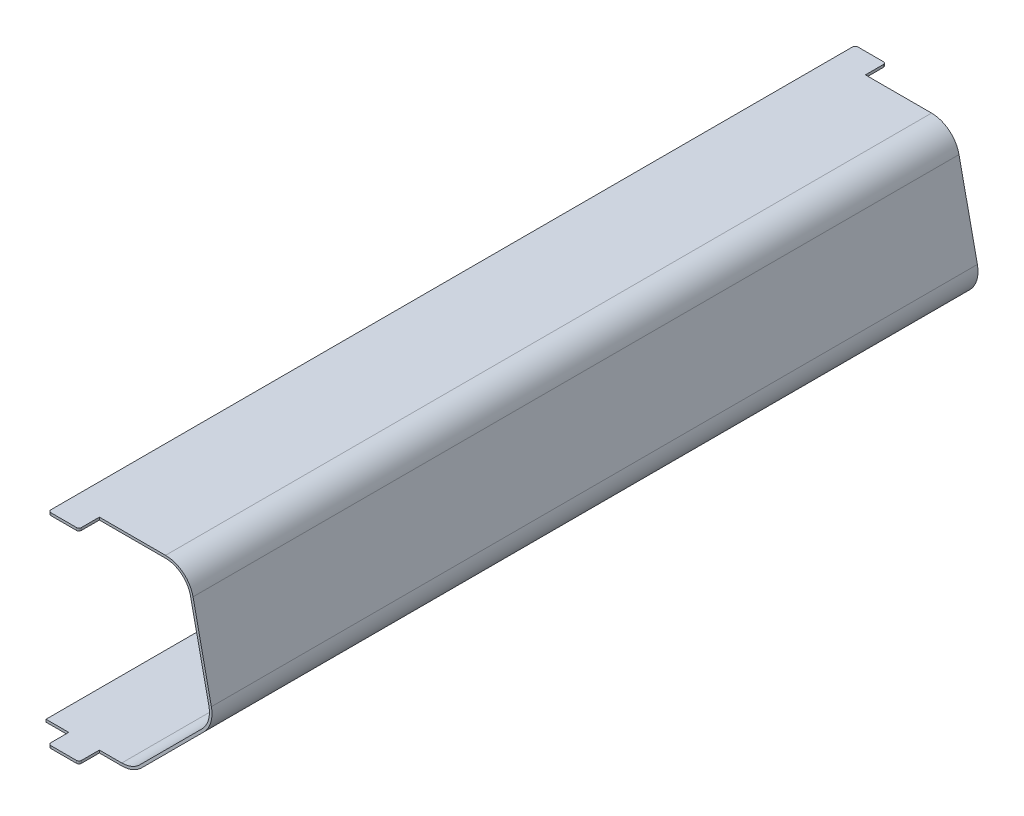
SolidWorks part; units mm, degrees
ref_plane "Front Plane" through (0, 0, 0) normal (0, 0, 1) x (1, 0, 0)
ref_plane "Top Plane" through (0, 0, 0) normal (0, 1, 0) x (1, 0, 0)
ref_plane "Right Plane" through (0, 0, 0) normal (1, 0, 0) x (0, 0, -1)
sketch "Sketch1" plane through (0, 0, 0) normal (0, 0, 1) x (1, 0, 0)
  line L0 (0, 0) -> (14.8381, 0)
  line L1 (18.3737, 1.4645) -> (30.5433, 13.6341)
  line L2 (31.8973, 18.2147) -> (28.3001, 35.0451)
  line L3 (23.4105, 39) -> (4.4547, 39)
  line L4 (0, -0.5) -> (14.8381, -0.5)
  line L5 (18.7272, 1.1109) -> (30.8969, 13.2806)
  line L6 (32.3863, 18.3193) -> (28.789, 35.1496)
  line L7 (23.4105, 39.5) -> (4.4547, 39.5)
  line L8 (4.4547, 39.5) -> (4.4547, 39)
  line L9 (0, 0) -> (0, -0.5)
  arc A0 (28.3001, 35.0451) -> (23.4105, 39) centre (23.4105, 34) ccw
  arc A1 (30.5433, 13.6341) -> (31.8973, 18.2147) centre (27.0078, 17.1697) ccw
  arc A2 (14.8381, 0) -> (18.3737, 1.4645) centre (14.8381, 5) ccw
  arc A3 (14.8381, -0.5) -> (18.7272, 1.1109) centre (14.8381, 5) ccw
  arc A4 (30.8969, 13.2806) -> (32.3863, 18.3193) centre (27.0078, 17.1697) ccw
  arc A5 (28.789, 35.1496) -> (23.4105, 39.5) centre (23.4105, 34) ccw
  point P8 (27.4547, 39)
  point P11 (32.4656, 15.5563)
  point P14 (16.9092, 0)
  dimension "D6" = 5
  dimension "D1" = 135
  dimension "D2" = 39
  dimension "D3" = 22
  dimension "D4" = 23
  dimension "D5" = 35
  dimension "D7" = 0.5
extrude "Boss-Extrude1" add sketch "Sketch1" against normal blind 150
sketch "Sketch2" plane through (0, 39.5, 0) normal (0, 1, 0) x (1, 0, 0)
  line L0 (4.4547, 150) -> (4.4547, 153.5)
  line L1 (4.9547, 154) -> (9.9547, 154)
  line L2 (10.4547, 153.5) -> (10.4547, 150)
  line L3 (23.4105, 150) -> (4.4547, 150) construction
  line L4 (0, 75) -> (23.4105, 75) construction
  line L5 (0, 150) -> (0, 0) construction
  line L6 (23.4105, 150) -> (23.4105, 0) construction
  line L7 (4.4547, 150) -> (10.4547, 150)
  line L8 (4.4547, 0) -> (10.4547, 0)
  line L9 (10.4547, -3.5) -> (10.4547, 0)
  line L10 (4.9547, -4) -> (9.9547, -4)
  line L11 (4.4547, 0) -> (4.4547, -3.5)
  arc A0 (9.9547, 154) -> (10.4547, 153.5) centre (9.9547, 153.5) cw
  arc A1 (4.4547, 153.5) -> (4.9547, 154) centre (4.9547, 153.5) cw
  arc A2 (9.9547, -4) -> (10.4547, -3.5) centre (9.9547, -3.5) ccw
  arc A3 (4.4547, -3.5) -> (4.9547, -4) centre (4.9547, -3.5) ccw
  point P9 (10.4547, 154)
  point P12 (4.4547, 154)
  point P27 (4.4547, -4)
  dimension "D3" = 0.5
  dimension "D1" = 4
  dimension "D2" = 6
extrude "Boss-Extrude2" add sketch "Sketch2" against normal blind 0.5
sketch "Sketch3" plane through (0, -0.5, 0) normal (0, -1, 0) x (1, 0, 0)
  line L0 (10.4547, 3.5) -> (10.4547, 0) construction
  line L1 (4.9547, 4) -> (9.9547, 4) construction
  line L2 (4.4547, -153.5) -> (4.4547, 3.5) construction
  line L3 (10.4547, 3.5) -> (10.4547, 0)
  line L4 (14.8381, 0) -> (0, 0)
  line L5 (0, 0) -> (0, -150)
  line L6 (0, -150) -> (14.8381, -150)
  line L7 (14.8381, -150) -> (14.8381, 0)
  line L8 (14.8381, 0) -> (0, 0)
  line L9 (0, 0) -> (0, -150)
  line L10 (0, -150) -> (14.8381, -150)
  line L11 (14.8381, -150) -> (14.8381, 0)
  line L12 (4.9547, 4) -> (9.9547, 4)
  line L13 (4.4547, -153.5) -> (4.4547, 3.5)
  line L14 (0, -75) -> (14.8381, -75) construction
  line L15 (4.9547, -154) -> (9.9547, -154)
  line L16 (10.4547, -153.5) -> (10.4547, -150)
  line L17 (14.8381, -150) -> (0, -150)
  arc A0 (10.4547, 3.5) -> (9.9547, 4) centre (9.9547, 3.5) ccw construction
  arc A1 (4.9547, 4) -> (4.4547, 3.5) centre (4.9547, 3.5) ccw construction
  arc A2 (10.4547, 3.5) -> (9.9547, 4) centre (9.9547, 3.5) ccw
  arc A3 (4.9547, 4) -> (4.4547, 3.5) centre (4.9547, 3.5) ccw
  arc A4 (4.9547, -154) -> (4.4547, -153.5) centre (4.9547, -153.5) cw
  arc A5 (10.4547, -153.5) -> (9.9547, -154) centre (9.9547, -153.5) cw
  line M5 (14.8381, 0) -> (0, 0)
  dimension "D1" = 0
extrude "Boss-Extrude3" add sketch "Sketch3" against normal blind 0.5 contours A5 L16 L10 L13 A4 L15 | L12 A3 L13 L3 A2 M5
